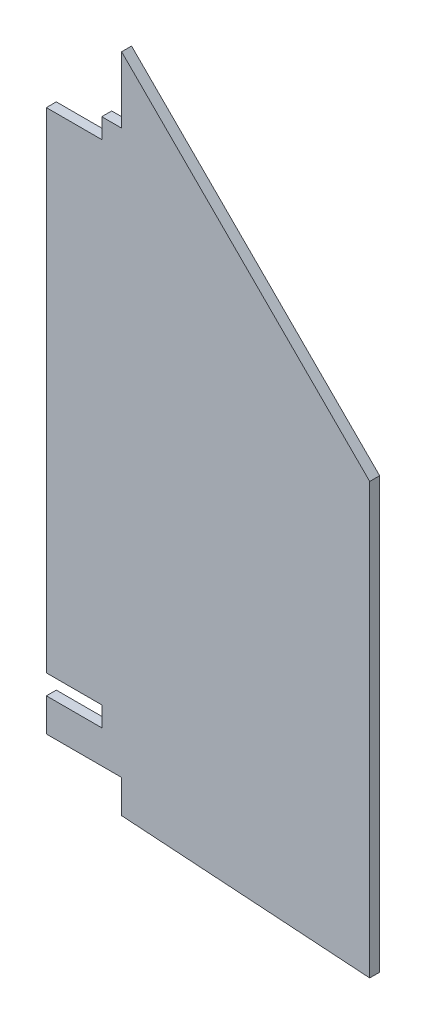
SolidWorks part; units mm, degrees
ref_plane "Front Plane" through (0, 0, 0) normal (0, 0, 1) x (1, 0, 0)
ref_plane "Top Plane" through (0, 0, 0) normal (0, 1, 0) x (1, 0, 0)
ref_plane "Right Plane" through (0, 0, 0) normal (1, 0, 0) x (0, 0, -1)
sketch "Sketch2" plane through (0, 0, 0) normal (0, 0, 1) x (1, 0, 0)
  line L0 (-119.9482, 12.6943) -> (-119.9482, 22.6943)
  line L1 (-44.9482, 7.6943) -> (-44.9482, 137.6943)
  line L2 (-119.9482, 212.6943) -> (152.0725, 212.6943) construction
  line L3 (-119.9482, 212.6943) -> (-44.9482, 137.6943)
  line L4 (-44.9482, 7.6943) -> (-119.9482, 12.6943)
  line L5 (-119.9482, 192.6943) -> (-125.9482, 192.6943)
  line L6 (-125.9482, 192.6943) -> (-125.9482, 186.6943)
  line L7 (-125.9482, 186.6943) -> (-142.6982, 186.6943)
  line L8 (-119.9482, 22.6943) -> (-142.6982, 22.6943)
  line L9 (-142.6982, 22.6943) -> (-142.6982, 32.6943)
  line L10 (-142.6982, 32.6943) -> (-125.9482, 32.6943)
  line L11 (-125.9482, 32.6943) -> (-125.9482, 38.6943)
  line L12 (-125.9482, 38.6943) -> (-142.6982, 38.6943)
  line L13 (-142.6982, 38.6943) -> (-142.6982, 186.6943)
  line L14 (-119.9482, 192.6943) -> (-119.9482, 212.6943)
  dimension "D1" = 200
  dimension "D2" = 130
  dimension "D3" = 75
  dimension "D4" = 45
  dimension "D5" = 20
  dimension "D6" = 6
  dimension "D7" = 6
  dimension "D8" = 16.75
  dimension "D9" = 10
  dimension "D10" = 6
  dimension "D11" = 10
extrude "Boss-Extrude2" add sketch "Sketch2" along normal blind 3
